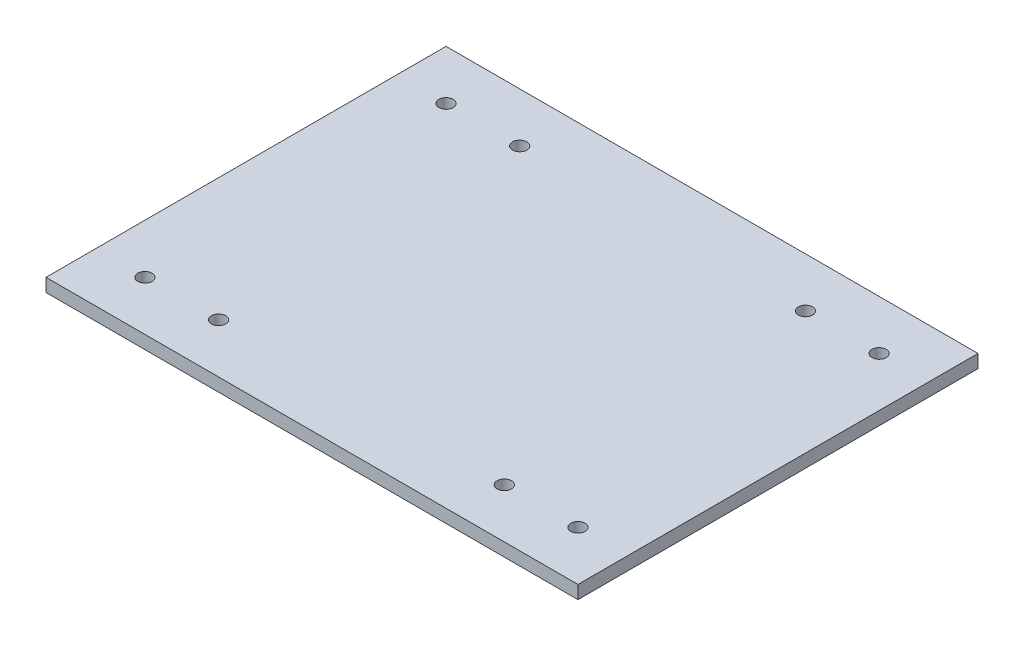
SolidWorks part; units mm, degrees
ref_plane "Front Plane" through (0, 0, 0) normal (0, 0, 1) x (1, 0, 0)
ref_plane "Top Plane" through (0, 0, 0) normal (0, 1, 0) x (1, 0, 0)
ref_plane "Right Plane" through (0, 0, 0) normal (1, 0, 0) x (0, 0, -1)
sketch "Sketch1" plane through (0, 0, 0) normal (0, 1, 0) x (1, 0, 0)
  line L1 (0, 0) -> (-242, 0)
  line L2 (0, 0) -> (0, 182)
  line L3 (0, 182) -> (-242, 182)
  line L4 (-242, 0) -> (-242, 182)
  circle A0 centre (-219.5, 159.5) radius 3.25
  circle A1 centre (-186, 159.5) radius 3.25
  circle A2 centre (-219.5, 22.5) radius 3.25
  circle A3 centre (-186, 22.5) radius 3.25
  circle A4 centre (-56, 22.5) radius 3.25
  circle A5 centre (-22.5, 22.5) radius 3.25
  circle A6 centre (-56, 159.5) radius 3.25
  circle A7 centre (-22.5, 159.5) radius 3.25
  point P20 (0, 0)
  point P21 (0, 0)
  point P22 (0, 0)
  point P23 (-150.3927, 13.3606)
  point P24 (0, 0)
  point P25 (0, 0)
  point P26 (0, 0)
  point P27 (0, 0)
  dimension "D1" = 6.5
  dimension "D2" = 22.5
  dimension "D3" = 22.5
  dimension "D4" = 137
  dimension "D5" = 22.5
  dimension "D6" = 33.5
  dimension "D7" = 33.5
  dimension "D8" = 22.5
  dimension "D9" = 130
extrude "Boss-Extrude1" add sketch "Sketch1" along normal blind 6
